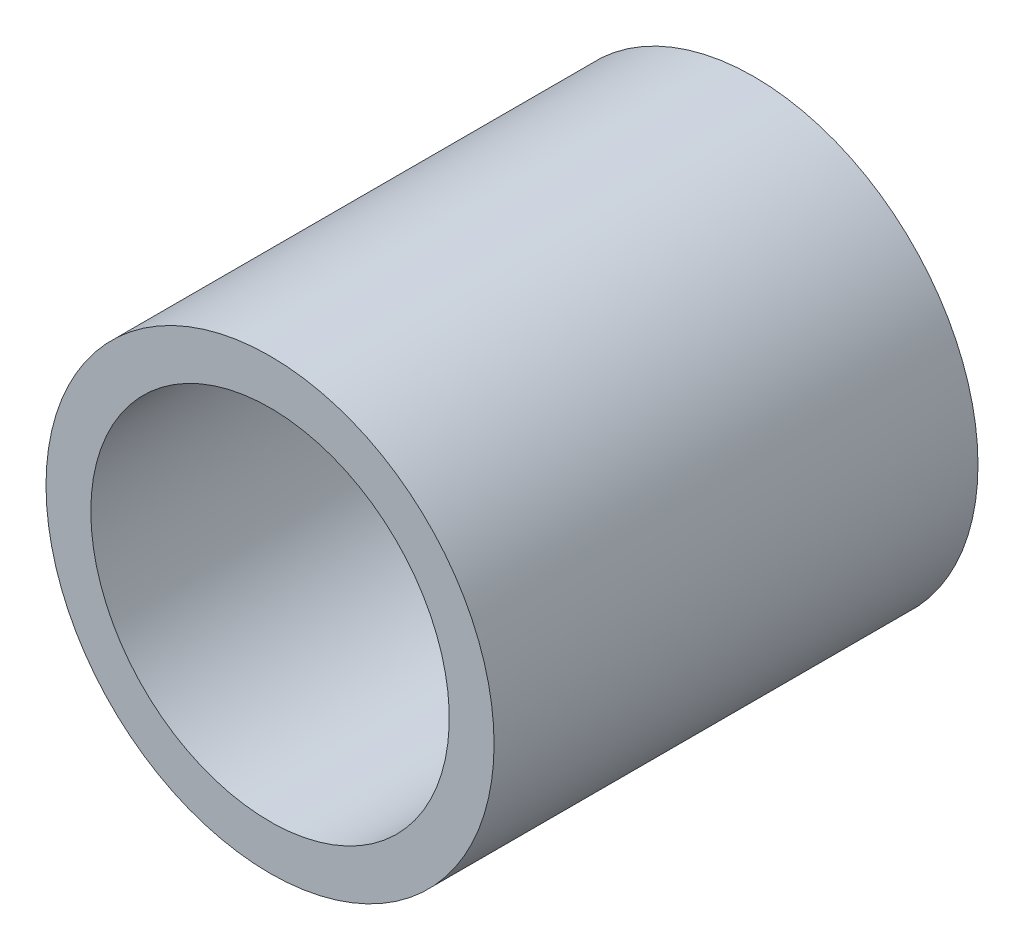
SolidWorks part; units mm, degrees
material "1060 合金"
ref_plane "正面" through (0, 0, 0) normal (0, 0, 1) x (1, 0, 0)
ref_plane "平面" through (0, 0, 0) normal (0, 1, 0) x (1, 0, 0)
ref_plane "右側面" through (0, 0, 0) normal (1, 0, 0) x (0, 0, -1)
sketch "ｽｹｯﾁ1" plane through (0, 0, 0) normal (0, 0, 1) x (1, 0, 0)
  circle A0 centre (0, 0) radius 5
  circle A1 centre (0, 0) radius 4
  dimension "D1" = 10
  dimension "D2" = 8
extrude "ﾎﾞｽ - 押し出し1" add sketch "ｽｹｯﾁ1" along normal blind 10.8
